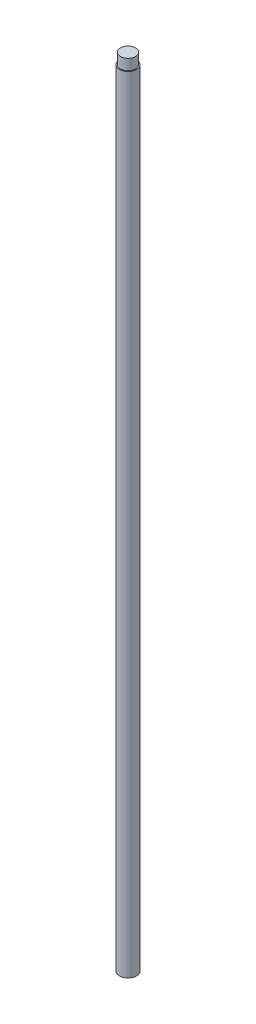
SolidWorks part; units mm, degrees
ref_plane "Plan de face" through (0, 0, 0) normal (0, 0, 1) x (1, 0, 0)
ref_plane "Plan de dessus" through (0, 0, 0) normal (0, 1, 0) x (1, 0, 0)
ref_plane "Plan de droite" through (0, 0, 0) normal (1, 0, 0) x (0, 0, -1)
sketch "Esquisse1" plane through (0, 0, 0) normal (0, 1, 0) x (1, 0, 0)
  circle A0 centre (0, 0) radius 4
  dimension "D1" = 8
extrude "Boss.-Extru.1" add sketch "Esquisse1" along normal blind 365
sketch "Esquisse2" plane through (0, 365, 0) normal (0, 1, 0) x (1, 0, 0)
  circle A0 centre (0, 0) radius 3.5
  dimension "D1" = 7
extrude "Boss.-Extru.2" add sketch "Esquisse2" along normal blind 5
